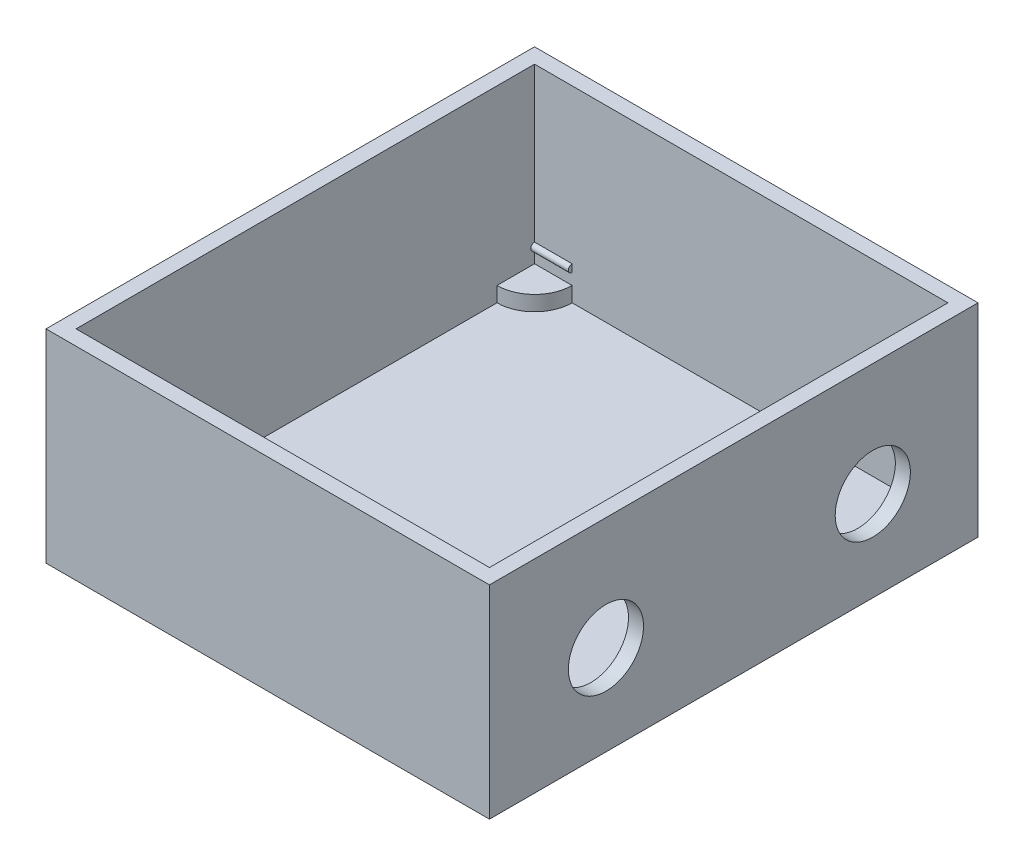
SolidWorks part; units mm, degrees
ref_plane "Спереди" through (0, 0, 0) normal (0, 0, 1) x (1, 0, 0)
ref_plane "Сверху" through (0, 0, 0) normal (0, 1, 0) x (1, 0, 0)
ref_plane "Справа" through (0, 0, 0) normal (1, 0, 0) x (0, 0, -1)
sketch "Эскиз1" plane through (0, 0, 0) normal (0, 1, 0) x (1, 0, 0)
  line L0 (-27.5, -30.5) -> (-27.5, 30.5)
  line L1 (-27.5, -30.5) -> (27.5, -30.5)
  line L2 (-27.5, 30.5) -> (27.5, 30.5)
  line L3 (27.5, -30.5) -> (27.5, 30.5)
  line L4 (-27.5, -30.5) -> (27.5, 30.5) construction
  line L5 (-27.5, 30.5) -> (27.5, -30.5) construction
  line L6 (-29.5, -32.5) -> (-29.5, 32.5)
  line L7 (-29.5, -32.5) -> (29.5, -32.5)
  line L8 (-29.5, 32.5) -> (29.5, 32.5)
  line L9 (29.5, -32.5) -> (29.5, 32.5)
  line L10 (-29.5, -32.5) -> (29.5, 32.5) construction
  line L11 (-29.5, 32.5) -> (29.5, -32.5) construction
  point P1 (0, 0)
  point P2 (0, 0)
extrude "Бобышка-Вытянуть1" add sketch "Эскиз1" along normal blind 25
sketch "Эскиз2" plane through (0, 0, 0) normal (0, -1, 0) x (1, 0, 0)
  line L1 (29.5, 32.5) -> (-29.5, 32.5)
  line L2 (29.5, 32.5) -> (29.5, -32.5)
  line L3 (29.5, -32.5) -> (-29.5, -32.5)
  line L4 (-29.5, 32.5) -> (-29.5, -32.5)
  line L5 (29.5, 32.5) -> (-29.5, -32.5) construction
  line L6 (29.5, -32.5) -> (-29.5, 32.5) construction
  point P0 (0, 0)
extrude "Бобышка-Вытянуть2" add sketch "Эскиз2" along normal blind 2
sketch "Эскиз3" plane through (0, 0, 0) normal (0, 1, 0) x (1, 0, 0)
  line L0 (-27.5, 30.5) -> (-27.5, -30.5) construction
  line L1 (27.5, 30.5) -> (-27.5, 30.5) construction
  line L2 (-27.5, 25.5) -> (-27.5, 30.5)
  line L3 (-27.5, 30.5) -> (-22.5, 30.5)
  line L4 (0, 0) -> (0, 32.5) construction
  line L5 (29.5, 32.5) -> (-29.5, 32.5) construction
  line L6 (27.5, 30.5) -> (22.5, 30.5)
  line L7 (27.5, 25.5) -> (27.5, 30.5)
  line L8 (0, 0) -> (29.5, 0) construction
  line L9 (29.5, -32.5) -> (29.5, 32.5) construction
  line L10 (27.5, -25.5) -> (27.5, -30.5)
  line L11 (27.5, -30.5) -> (22.5, -30.5)
  line L12 (-27.5, -25.5) -> (-27.5, -30.5)
  line L13 (-27.5, -30.5) -> (-22.5, -30.5)
  arc A0 (-27.5, 25.5) -> (-22.5, 30.5) centre (-27.5, 30.5) ccw
  arc A1 (27.5, 25.5) -> (22.5, 30.5) centre (27.5, 30.5) cw
  arc A2 (27.5, -25.5) -> (22.5, -30.5) centre (27.5, -30.5) ccw
  arc A3 (-27.5, -25.5) -> (-22.5, -30.5) centre (-27.5, -30.5) cw
extrude "Бобышка-Вытянуть3" add sketch "Эскиз3" along normal blind 2
sketch "Эскиз4" plane through (27.5, 0, 0) normal (-1, 0, 0) x (0, 0, 1)
  line L0 (30.5, 10) -> (-30.5, 10) construction
  line L1 (30.5, 2) -> (17, 2)
  line L2 (30.5, 2) -> (30.5, 10)
  line L3 (30.5, 10) -> (17, 10)
  line L4 (17, 2) -> (17, 10)
  circle A0 centre (17, 10) radius 5
  circle A1 centre (-18.5, 10) radius 5
  point P4 (0, 0)
  point P9 (0, 0)
extrude "Вырез-Вытянуть1" cut sketch "Эскиз4" against normal through all contours L3 A0 L4 | L4 A0 L3 | L4 L0 A0 | A1 L0 | L0 A1
sketch "Эскиз5" plane through (0, 0, 30.5) normal (0, 0, -1) x (-1, 0, 0)
  line L0 (-27.5, 4) -> (27.5, 4) construction
  line L1 (0, 0) -> (0, 5.9618) construction
  line L2 (-27.5, 4) -> (-22.5, 4)
  line L3 (-27.5, 4) -> (-27.5, 3.5)
  line L4 (-27.5, 3.5) -> (-22.5, 3.5)
  line L5 (-22.5, 4) -> (-22.5, 3.5)
  line L6 (22.5, 4) -> (22.5, 3.5)
  line L7 (27.5, 4) -> (22.5, 4)
  line L8 (27.5, 4) -> (27.5, 3.5)
  line L9 (27.5, 3.5) -> (22.5, 3.5)
revolve "Повернуть1" add sketch "Эскиз5" angle 180 about L0
sketch "Эскиз7" plane through (0, 0, -30.5) normal (0, 0, 1) x (1, 0, 0)
  line L0 (-27.5, 4) -> (27.5, 4) construction
  line L1 (0, 0) -> (0, 9.2985) construction
  line L2 (-27.5, 4) -> (-22.5, 4)
  line L3 (-27.5, 4) -> (-27.5, 3.5)
  line L4 (-27.5, 3.5) -> (-22.5, 3.5)
  line L5 (-22.5, 4) -> (-22.5, 3.5)
  line L6 (27.5, 4) -> (27.5, 3.5)
  line L7 (27.5, 4) -> (22.5, 4)
  line L8 (22.5, 4) -> (22.5, 3.5)
  line L9 (27.5, 3.5) -> (22.5, 3.5)
revolve "Повернуть2" add sketch "Эскиз7" angle 180 about L0
